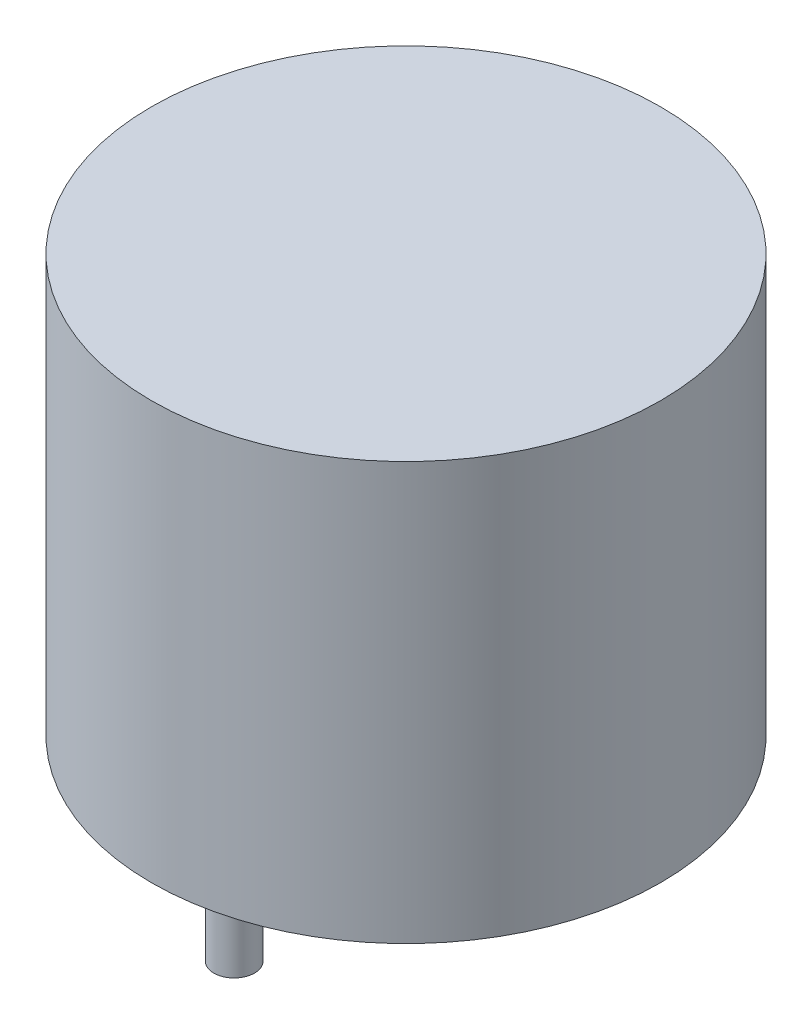
SolidWorks part; units mm, degrees
ref_plane "Front Plane" through (0, 0, 0) normal (0, 0, 1) x (1, 0, 0)
ref_plane "Top Plane" through (0, 0, 0) normal (0, 1, 0) x (1, 0, 0)
ref_plane "Right Plane" through (0, 0, 0) normal (1, 0, 0) x (0, 0, -1)
sketch "Эскиз1" plane through (0, 0, 0) normal (0, 1, 0) x (1, 0, 0)
  circle A0 centre (0, 0) radius 10
  dimension "D1" = 20
extrude "Бобышка-Вытянуть1" add sketch "Эскиз1" along normal blind 16.4
sketch "Эскиз2" plane through (0, 0, 0) normal (0, -1, 0) x (1, 0, 0)
  line L0 (0, 0) -> (0, 6.75) construction
  line L1 (0, 0) -> (-6.75, 0) construction
  circle A1 centre (0, 6.75) radius 0.8
  circle A2 centre (-6.75, 0) radius 0.8
  circle A3 centre (0, 0) radius 10 construction
  dimension "D1" = 1.6
  dimension "D2" = 6.75
extrude "Бобышка-Вытянуть2" add sketch "Эскиз2" along normal blind 4.3
